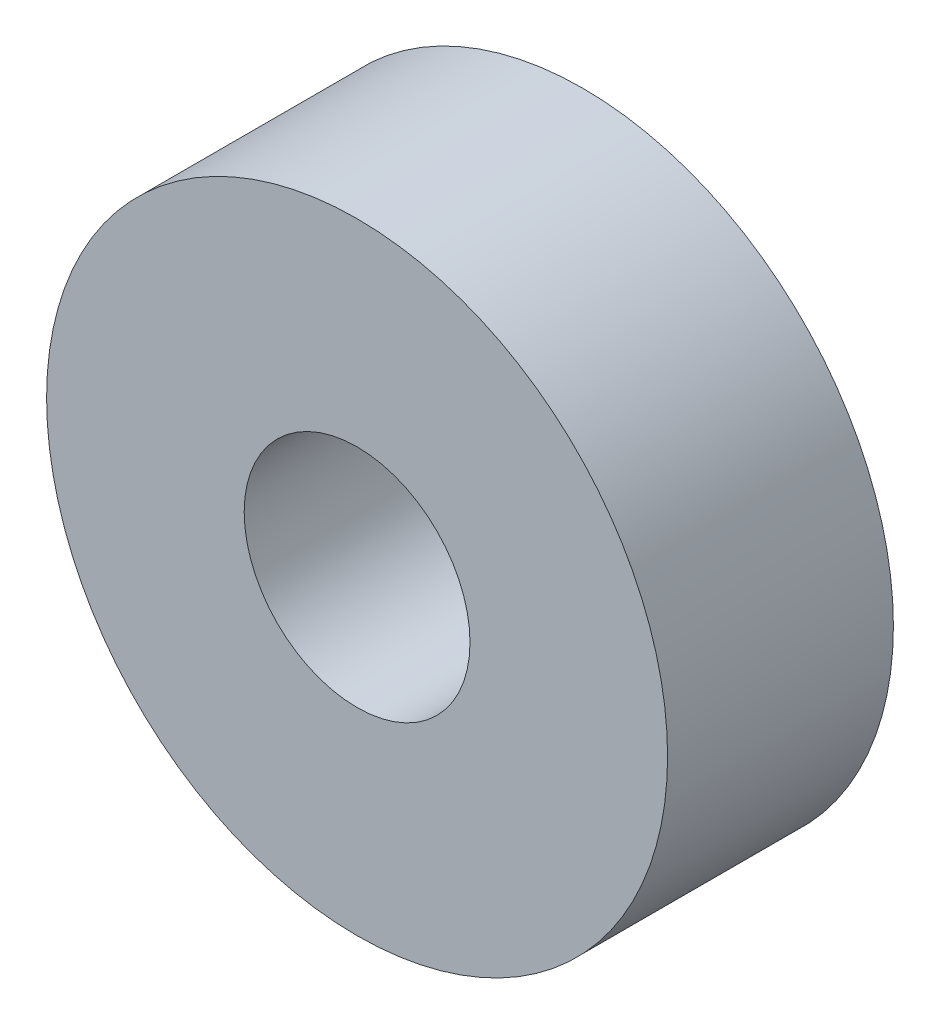
SolidWorks part; units mm, degrees
material "Stainless Steel (ferritic)"
ref_plane "Front Plane" through (0, 0, 0) normal (0, 0, 1) x (1, 0, 0)
ref_plane "Top Plane" through (0, 0, 0) normal (0, 1, 0) x (1, 0, 0)
ref_plane "Right Plane" through (0, 0, 0) normal (1, 0, 0) x (0, 0, -1)
ref_plane "Plane1" through (0, 0, 0) normal (0, -1, 0) x (1, 0, 0)
sketch "Sketch1" plane through (0, 0, 0) normal (0, -1, 0) x (1, 0, 0)
  line L0 (11, 8) -> (4, 8)
  line L1 (4, 8) -> (4, 0)
  line L2 (4, 0) -> (11, 0)
  line L3 (11, 0) -> (11, 8)
  line L4 (0, 8) -> (0, 0) construction
revolve "Revolve1" add sketch "Sketch1" angle 360 about L4
